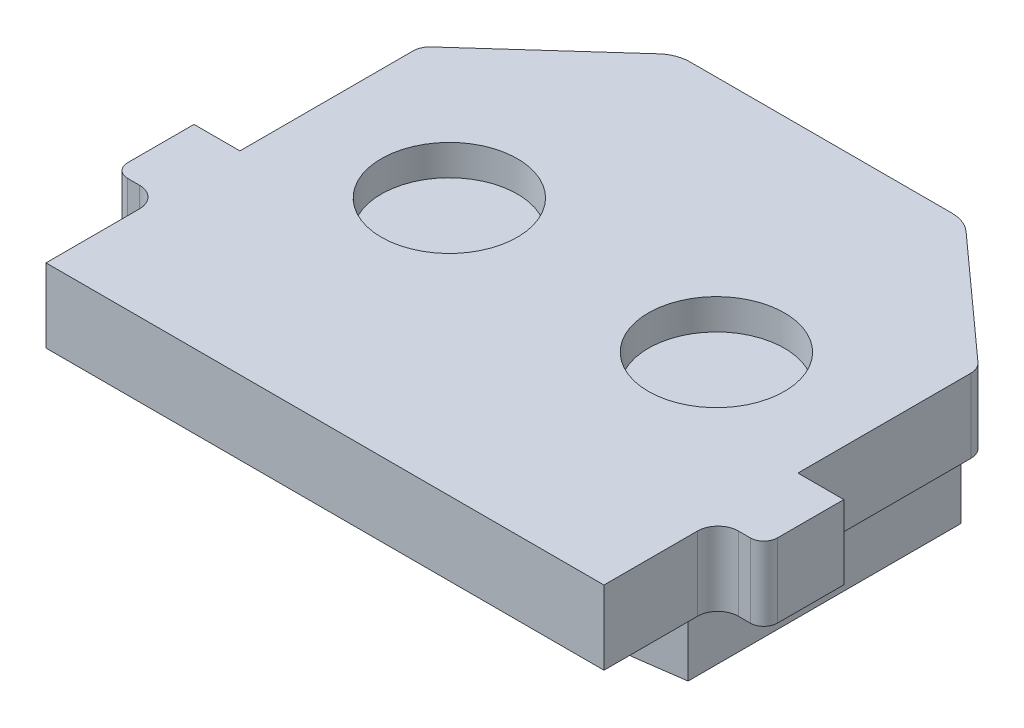
SolidWorks part; units mm, degrees
ref_plane "Front Plane" through (0, 0, 0) normal (0, 0, 1) x (1, 0, 0)
ref_plane "Top Plane" through (0, 0, 0) normal (0, 1, 0) x (1, 0, 0)
ref_plane "Right Plane" through (0, 0, 0) normal (1, 0, 0) x (0, 0, -1)
sketch "Sketch1" plane through (0, 0, 0) normal (0, 1, 0) x (1, 0, 0)
  line L0 (0, 0) -> (0, 15.9842) construction
  line L1 (-20.828, -18.5166) -> (20.828, -18.5166)
  line L2 (-20.828, -18.5166) -> (-20.828, -11.5316)
  line L3 (-9.779, 18.5166) -> (9.779, 18.5166)
  line L4 (20.828, -18.5166) -> (20.828, -11.5316)
  line L5 (-20.828, -18.5166) -> (15.7597, 14.0108) construction
  line L6 (-15.7597, 14.0108) -> (20.828, -18.5166) construction
  line L7 (-23.241, -10.0076) -> (-22.352, -10.0076)
  line L8 (-24.257, -8.9916) -> (-24.257, -4.0386)
  line L9 (-24.257, -4.0386) -> (-20.828, -4.0386)
  line L11 (24.257, -4.0386) -> (20.828, -4.0386)
  line L13 (23.241, -10.0076) -> (22.352, -10.0076)
  line L14 (24.257, -8.9916) -> (24.257, -4.0386)
  line L15 (-20.828, -4.0386) -> (-20.828, 8.8833)
  line L16 (20.828, 8.8833) -> (20.828, -4.0386)
  line L17 (-11.4783, 17.8645) -> (-20.4076, 9.8273)
  line L18 (-9.779, 18.5166) -> (9.779, 18.5166)
  line L22 (11.4783, 17.8645) -> (20.4076, 9.8273)
  arc A0 (22.352, -10.0076) -> (20.828, -11.5316) centre (22.352, -11.5316) ccw
  arc A1 (-22.352, -10.0076) -> (-20.828, -11.5316) centre (-22.352, -11.5316) cw
  arc A2 (23.241, -10.0076) -> (24.257, -8.9916) centre (23.241, -8.9916) ccw
  arc A3 (-23.241, -10.0076) -> (-24.257, -8.9916) centre (-23.241, -8.9916) cw
  arc A4 (-9.779, 18.5166) -> (-11.4783, 17.8645) centre (-9.779, 15.9766) ccw
  arc A5 (9.779, 18.5166) -> (11.4783, 17.8645) centre (9.779, 15.9766) cw
  arc A6 (-20.4076, 9.8273) -> (-20.828, 8.8833) centre (-19.558, 8.8833) ccw
  arc A7 (20.4076, 9.8273) -> (20.828, 8.8833) centre (19.558, 8.8833) cw
  point P0 (0, 0)
  point P22 (24.257, -10.0076)
  point P25 (-24.257, -10.0076)
  point P36 (-20.828, 9.4489)
  point P39 (20.828, 9.4489)
  dimension "D1" = 1.524
  dimension "D2" = 1.016
  dimension "D7" = 2.54
  dimension "D10" = 1.27
  dimension "D3" = 3.429
  dimension "D4" = 5.969
  dimension "D5" = 14.478
  dimension "D6" = 24.257
  dimension "D8" = 9.779
  dimension "D9" = 138.01
  dimension "D11" = 18.5166
  dimension "D12" = 20.828
  dimension "D13" = 18.5166
  dimension "D14" = 10.0076
extrude "Boss-Extrude1" add sketch "Sketch1" along normal blind 5.5118 contours A7 L22 A5 L3 A4 L17 A6 L15 L9 L8 A3 L7 A1 L2 L1 L4 A0 L13 A2 L14 L11 L16
sketch "Sketch2" plane through (0, 5.5118, 0) normal (0, 1, 0) x (1, 0, 0)
  line L1 (-9.779, 18.5166) -> (9.779, 18.5166) construction
  circle A0 centre (-9.9695, 0.7366) radius 5.08
  circle A1 centre (9.9695, 0.7366) radius 5.08
  point P4 (0, 0)
  point P7 (0, 0)
  point P8 (0, 0)
  point P9 (0, 0)
  point P12 (0, 0)
  dimension "D1" = 10.16
  dimension "D2" = 10.16
  dimension "D3" = 17.78
  dimension "D4" = 19.939
  dimension "D5" = 9.9695
extrude "Cut-Extrude1" cut sketch "Sketch2" against normal blind 2.286
sketch "Sketch3" plane through (0, 0, 0) normal (0, -1, 0) x (1, 0, 0)
  line L3 (10.795, -17.2466) -> (-10.795, -17.2466)
  line L4 (-9.779, -18.5166) -> (9.779, -18.5166) construction
  line L5 (10.795, -17.2466) -> (20.0456, -8.9202)
  line L6 (-10.795, -17.2466) -> (-20.0456, -8.9202)
  line L9 (-11.4783, -17.8645) -> (-20.4076, -9.8273) construction
  line L10 (11.4783, -17.8645) -> (20.4076, -9.8273) construction
  line L11 (-23.241, 10.0076) -> (-22.352, 10.0076) construction
  line L13 (20.0456, -8.9202) -> (20.0456, 11.4554)
  line L24 (-20.0456, -8.9202) -> (-20.0456, 11.4554)
  arc A0 (20.0456, 11.4554) -> (-20.0456, 11.4554) centre (0, -120.6362) ccw
  dimension "D7" = 133.604
  dimension "D6" = 120.6362
  dimension "D8" = 130.6438
  dimension "D1" = 1.27
  dimension "D2" = 21.59
  dimension "D3" = 10.795
  dimension "D4" = 12.446
  dimension "D5" = 12.446
extrude "Boss-Extrude2" add sketch "Sketch3" along normal blind 4.6228
